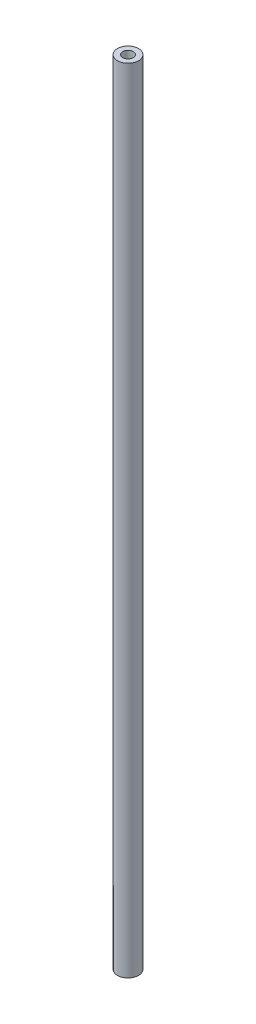
SolidWorks part; units mm, degrees
ref_plane "Front Plane" through (0, 0, 0) normal (0, 0, 1) x (1, 0, 0)
ref_plane "Top Plane" through (0, 0, 0) normal (0, 1, 0) x (1, 0, 0)
ref_plane "Right Plane" through (0, 0, 0) normal (1, 0, 0) x (0, 0, -1)
sketch "Sketch2" plane through (0, 0, 0) normal (0, 1, 0) x (1, 0, 0)
  circle A0 centre (0, 0) radius 0.0508
  circle A1 centre (0, 0) radius 0.1016
  dimension "D1" = 0.1016
  dimension "D2" = 0.2032
extrude "Boss-Extrude1" add sketch "Sketch2" along normal blind 7.62
